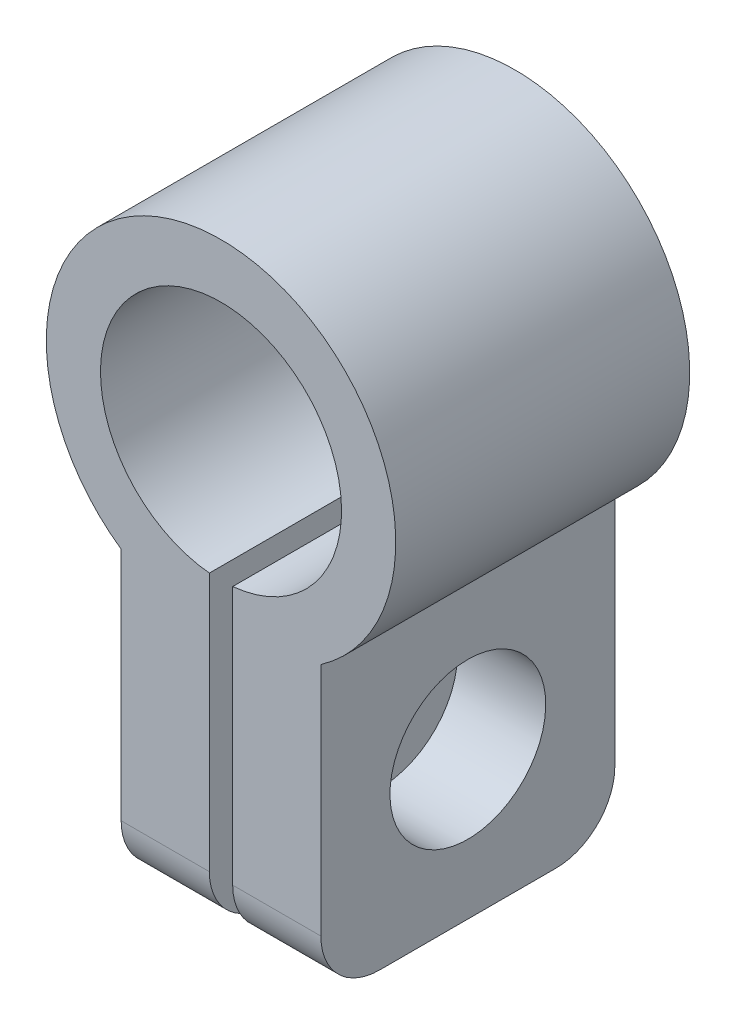
SolidWorks part; units mm, degrees
ref_plane "Front Plane" through (0, 0, 0) normal (0, 0, 1) x (1, 0, 0)
ref_plane "Top Plane" through (0, 0, 0) normal (0, 1, 0) x (1, 0, 0)
ref_plane "Right Plane" through (0, 0, 0) normal (1, 0, 0) x (0, 0, -1)
sketch "Sketch1" plane through (0, 0, 0) normal (0, 0, 1) x (1, 0, 0)
  line L0 (0, 0) -> (0, -2.6157) construction
  line L1 (-0.3968, -4.0807) -> (-0.3968, -14.878)
  line L2 (-0.3968, -14.878) -> (-3.3968, -14.878)
  line L3 (-3.3968, -14.878) -> (-3.3968, -4.878)
  line L4 (0.3968, -4.0807) -> (0.3968, -14.878)
  line L5 (0.3968, -14.878) -> (3.3968, -14.878)
  line L6 (3.3968, -14.878) -> (3.3968, -4.878)
  circle A0 centre (0, 0) radius 4 construction
  arc A1 (0.3968, -4.0807) -> (-0.3968, -4.0807) centre (0, 0) ccw
  arc A3 (3.3968, -4.878) -> (-3.3968, -4.878) centre (0, 0) ccw
  dimension "D1" = 8
  dimension "D2" = 8.2
  dimension "D3" = 5.9442
  dimension "D4" = 3
  dimension "D5" = 10
extrude "Boss-Extrude1" add sketch "Sketch1" along normal blind 10
sketch "Sketch2" plane through (3.3968, 0, 0) normal (1, 0, 0) x (0, 0, -1)
  line L0 (-10, -14.878) -> (0, -4.878)
  circle A0 centre (-5, -9.878) radius 2.65
  dimension "D1" = 5.3
extrude "Cut-Extrude1" cut sketch "Sketch2" against normal blind 10 contours L0 A0 | L0 A0
ref_plane "Plane1" through (-5.9442, 0, 0) normal (-1, 0, 0) x (0, 0, 1)
sketch "Sketch3" plane through (-5.9442, 0, 0) normal (-1, 0, 0) x (0, 0, 1)
  circle A0 centre (5, 0.5331) radius 4
  dimension "D1" = 8
ref_plane "Plane2" through (5.9442, 0, 0) normal (1, 0, 0) x (0, 0, -1)
fillet "Fillet1" radius 2 4 edges at (-1.8968, -14.878, 0) (1.8968, -14.878, 0) (-1.8968, -14.878, 10) (1.8968, -14.878, 10)
